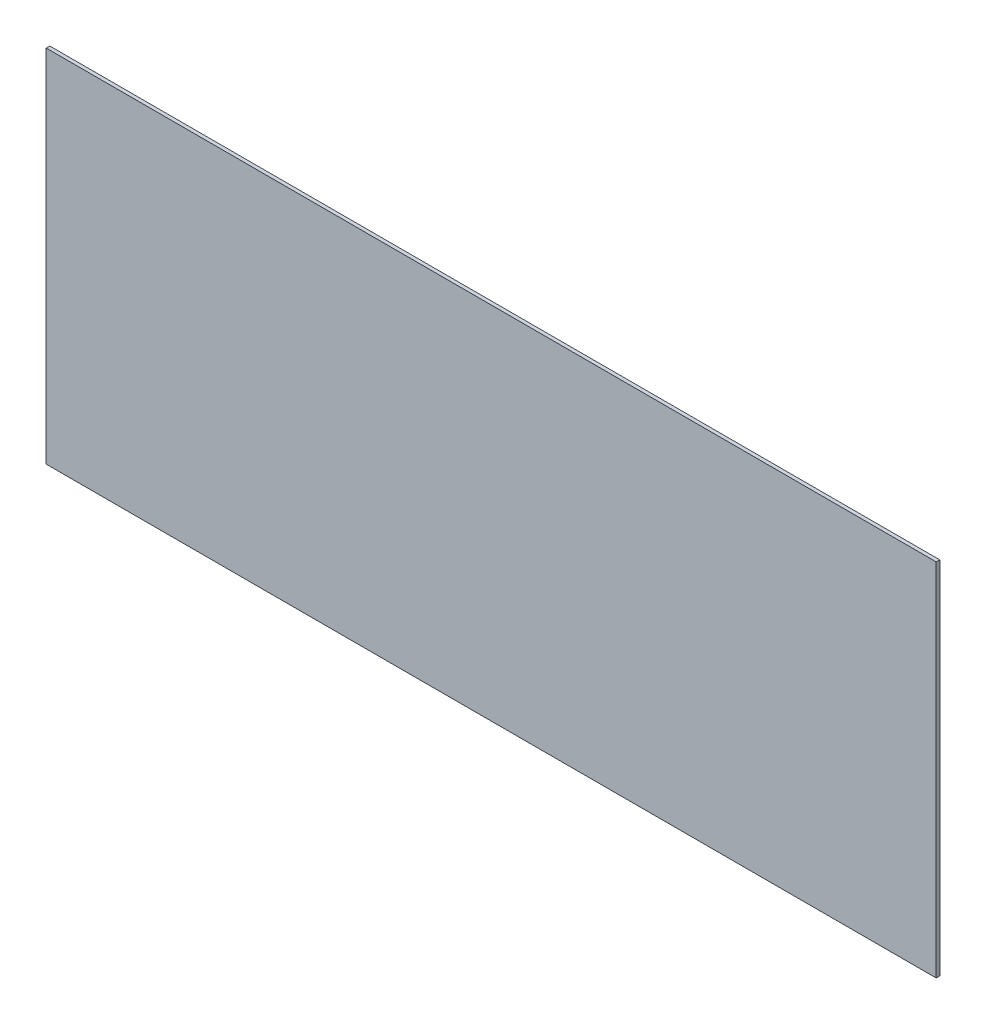
SolidWorks part; units mm, degrees
ref_plane "Plano frontal" through (0, 0, 0) normal (0, 0, 1) x (1, 0, 0)
ref_plane "Plano superior" through (0, 0, 0) normal (0, 1, 0) x (1, 0, 0)
ref_plane "Plano direito" through (0, 0, 0) normal (1, 0, 0) x (0, 0, -1)
sketch "Esboço1" plane through (0, 0, 0) normal (0, 0, 1) x (1, 0, 0)
  line L0 (250, 101.23) -> (-250, -101.23) construction
  line L1 (-250, 101.23) -> (250, 101.23)
  line L2 (-250, 101.23) -> (-250, -101.23)
  line L3 (-250, -101.23) -> (250, -101.23)
  line L4 (250, 101.23) -> (250, -101.23)
  dimension "D1" = 202.46
  dimension "D2" = 500
extrude "Ressalto-extrusão1" add sketch "Esboço1" along normal blind 2
